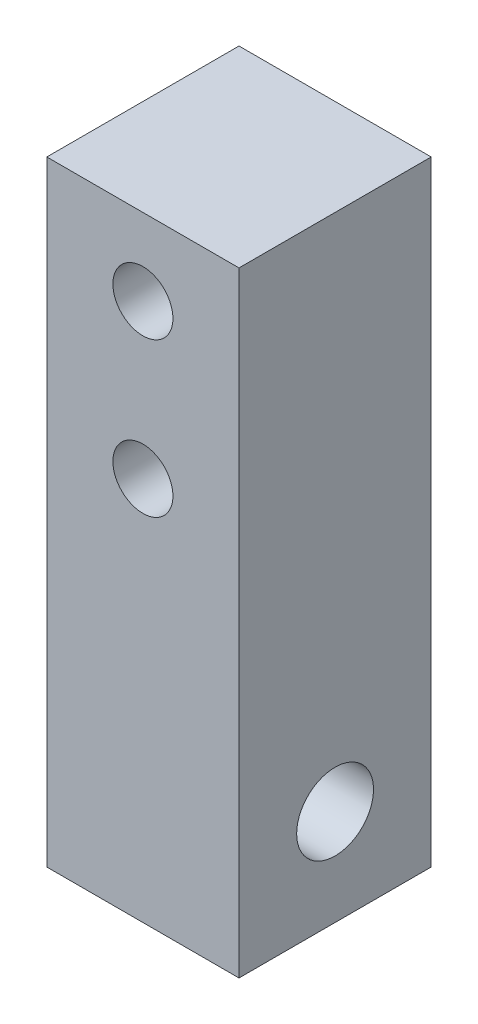
SolidWorks part; units mm, degrees
ref_plane "Front Plane" through (0, 0, 0) normal (0, 0, 1) x (1, 0, 0)
ref_plane "Top Plane" through (0, 0, 0) normal (0, 1, 0) x (1, 0, 0)
ref_plane "Right Plane" through (0, 0, 0) normal (1, 0, 0) x (0, 0, -1)
sketch "Sketch1" plane through (0, 0, 0) normal (0, 0, 1) x (1, 0, 0)
  line L1 (0, 0) -> (31.75, 0)
  line L2 (0, 0) -> (0, 101.6)
  line L3 (0, 101.6) -> (31.75, 101.6)
  line L4 (31.75, 0) -> (31.75, 101.6)
  dimension "D1" = 101.6
  dimension "D2" = 31.75
extrude "Boss-Extrude1" add sketch "Sketch1" along normal blind 31.75
sketch "Sketch2" plane through (0, 0, 31.75) normal (0, 0, 1) x (1, 0, 0)
  line L0 (31.75, 101.6) -> (0, 101.6) construction
  circle A0 centre (15.875, 88.9) radius 4.9609
  circle A1 centre (15.875, 63.5) radius 4.9609
  point P6 (15.875, 101.6)
  dimension "D1" = 9.9219
  dimension "D2" = 12.7
  dimension "D3" = 25.4
extrude "Cut-Extrude1" cut sketch "Sketch2" against normal through all
sketch "Sketch3" plane through (0, 0, 0) normal (-1, 0, 0) x (0, 0, 1)
  line L0 (31.75, 0) -> (0, 0) construction
  circle A0 centre (15.875, 15.875) radius 6.35
  point P4 (15.875, 0)
  dimension "D2" = 12.7
  dimension "D1" = 15.875
extrude "Cut-Extrude2" cut sketch "Sketch3" against normal through all
